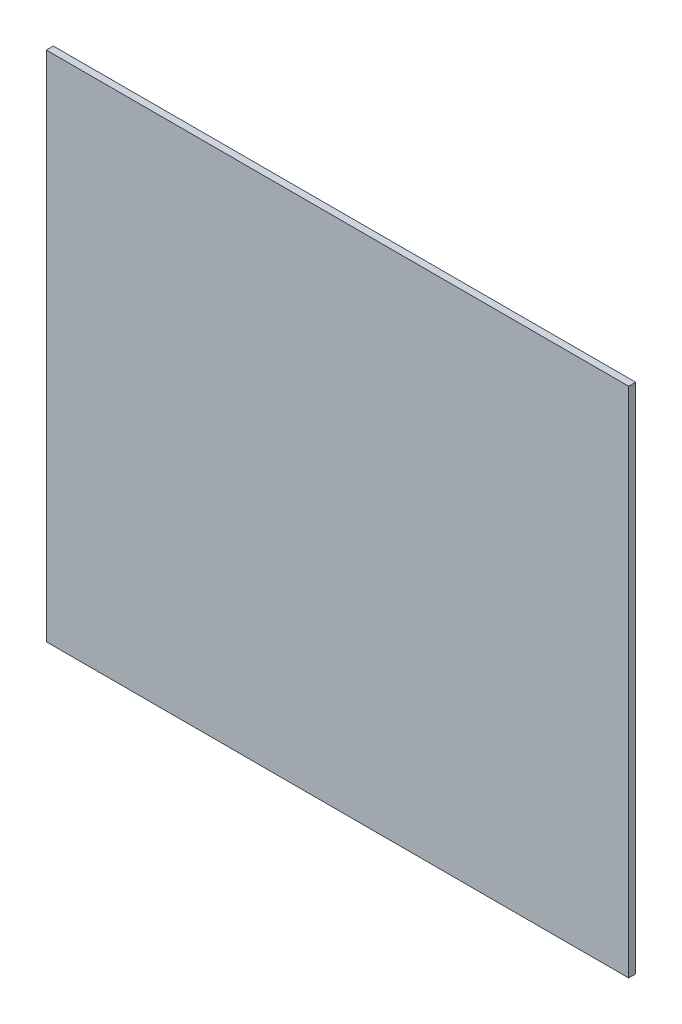
SolidWorks part; units mm, degrees
ref_plane "Top plane" through (0, 0, 0) normal (0, 0, 1) x (1, 0, 0)
ref_plane "Right plane" through (0, 0, 0) normal (0, 1, 0) x (1, 0, 0)
ref_plane "Front plane" through (0, 0, 0) normal (1, 0, 0) x (0, 0, -1)
sketch "Sketch1" plane through (0, 0, 0) normal (0, 0, 1) x (1, 0, 0)
  line L1 (-89.5388, 189.8549) -> (160.4612, 189.8549)
  line L2 (-89.5388, 189.8549) -> (-89.5388, -30.1451)
  line L3 (-89.5388, -30.1451) -> (160.4612, -30.1451)
  line L4 (160.4612, 189.8549) -> (160.4612, -30.1451)
extrude "Boss-Extrude1" add sketch "Sketch1" along normal blind 3
ref_plane "Plane1" through (0, 129.8549, 0) normal (0, 1, 0) x (1, 0, 0)
sketch "Sketch2" plane through (0, 129.8549, 0) normal (0, 1, 0) x (1, 0, 0)
  line L0 (131.0214, 8.23) -> (131.0214, 0)
  line L2 (160.4612, 0) -> (-89.5388, 0) construction
  line L3 (131.0214, 0) -> (117.4839, 0)
  line L4 (117.4839, 0) -> (117.2914, 8.23)
  arc A0 (131.0214, 8.23) -> (117.2989, 7.9091) centre (124.1564, 8.23) ccw
  dimension "13.7" = 13.73
extrude "Extrude-Thin1" add sketch "Sketch2" along normal blind 2 thin contours L0 A0 L4 L3
